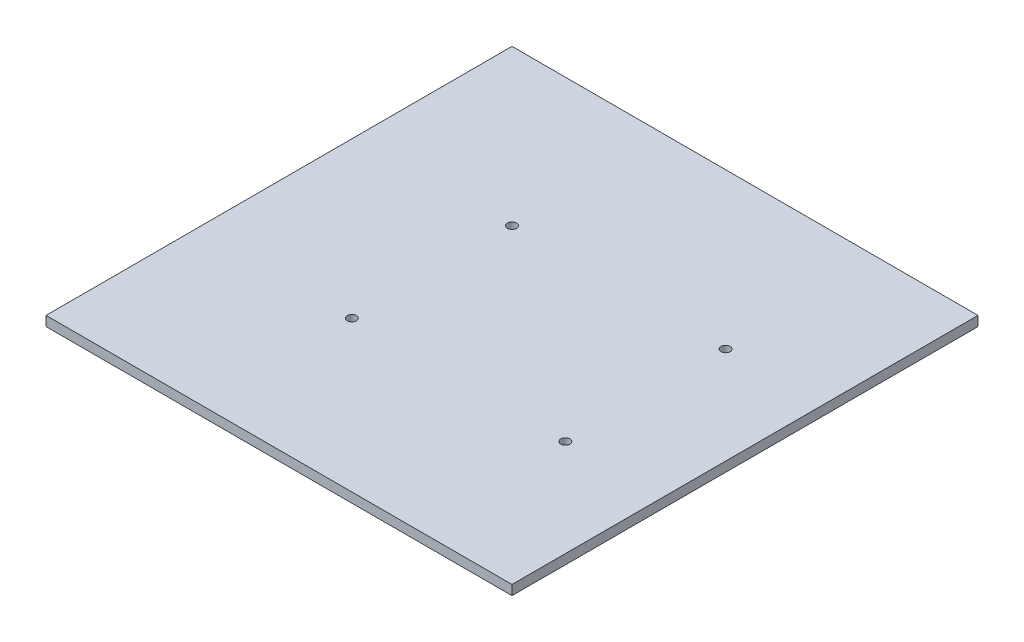
SolidWorks part; units mm, degrees
material "Thornel Mat VMA"
ref_plane "Front Plane" through (0, 0, 0) normal (0, 0, 1) x (1, 0, 0)
ref_plane "Top Plane" through (0, 0, 0) normal (0, 1, 0) x (1, 0, 0)
ref_plane "Right Plane" through (0, 0, 0) normal (1, 0, 0) x (0, 0, -1)
sketch "Sketch1" plane through (0, 0, 0) normal (0, 1, 0) x (1, 0, 0)
  line L1 (-76.2, -76.2) -> (76.2, -76.2)
  line L2 (-76.2, -76.2) -> (-76.2, 76.2)
  line L3 (-76.2, 76.2) -> (76.2, 76.2)
  line L4 (76.2, -76.2) -> (76.2, 76.2)
  line L5 (-76.2, -76.2) -> (76.2, 76.2) construction
  line L6 (-76.2, 76.2) -> (76.2, -76.2) construction
  point P0 (0, 0)
  dimension "D1" = 152.4
  dimension "D2" = 152.4
extrude "Boss-Extrude1" add sketch "Sketch1" along normal blind 3.175
sketch "Sketch2" plane through (0, 3.175, 0) normal (0, 1, 0) x (1, 0, 0)
  circle A0 centre (-25.4, 25.4) radius 1.5 construction
  circle A1 centre (-25.4, -26.9875) radius 1.5 construction
  circle A2 centre (44.45, 25.4) radius 1.5 construction
  circle A3 centre (44.45, -26.9875) radius 1.5 construction
  circle A8 centre (-25.4, 25.4) radius 1.5
  circle A9 centre (-25.4, -26.9875) radius 1.5
  circle A10 centre (44.45, 25.4) radius 1.5
  circle A11 centre (44.45, -26.9875) radius 1.5
extrude "Cut-Extrude1" cut sketch "Sketch2" against normal through all
equation "\"D2@Sketch1\"=\"D1@Sketch1\""
